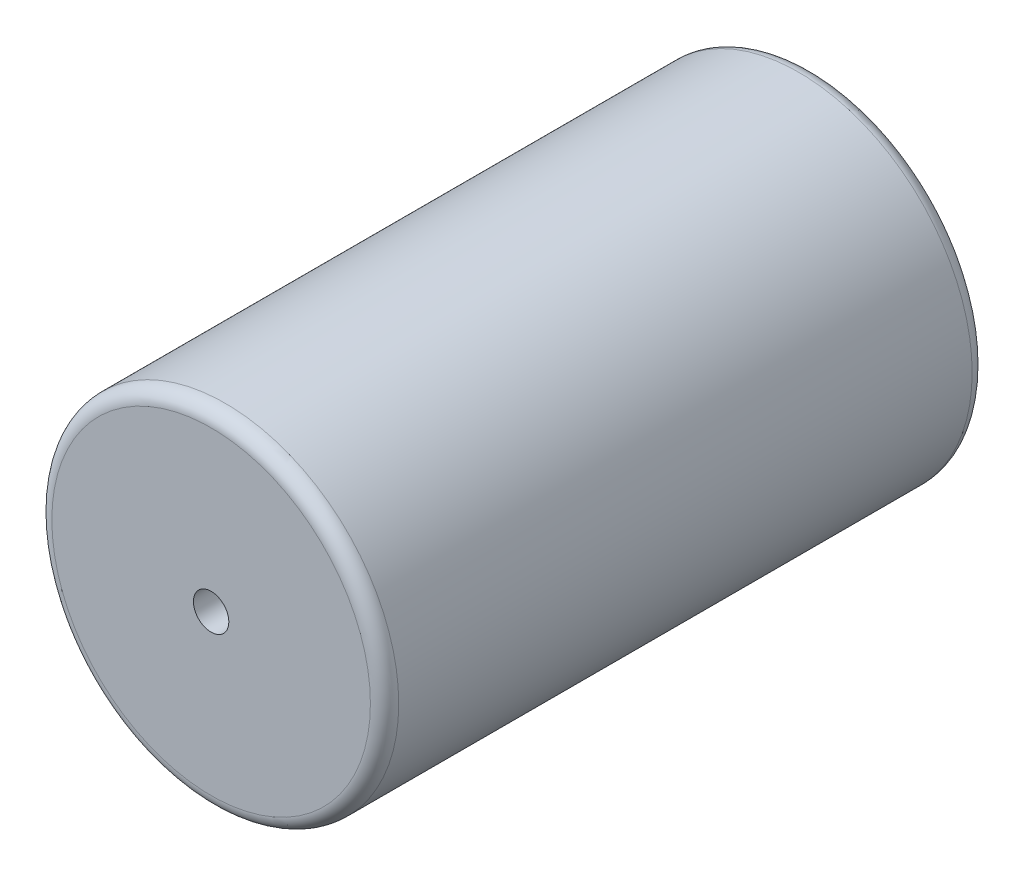
SolidWorks part; units mm, degrees
ref_plane "Front Plane" through (0, 0, 0) normal (0, 0, 1) x (1, 0, 0)
ref_plane "Top Plane" through (0, 0, 0) normal (0, 1, 0) x (1, 0, 0)
ref_plane "Right Plane" through (0, 0, 0) normal (1, 0, 0) x (0, 0, -1)
sketch "Sketch1" plane through (0, 0, 0) normal (0, 0, 1) x (1, 0, 0)
  circle A0 centre (0, 0) radius 24.5
  dimension "D1" = 49
extrude "Boss-Extrude1" add sketch "Sketch1" along normal blind 85
fillet "Fillet1" radius 2 2 edges at (24.5, 0, 0) (24.5, 0, 85)
sketch "Sketch2" plane through (0, 0, 85) normal (0, 0, 1) x (1, 0, 0)
  circle A0 centre (0, 0) radius 2.5
  dimension "D1" = 5
extrude "Cut-Extrude1" cut sketch "Sketch2" against normal blind 7
